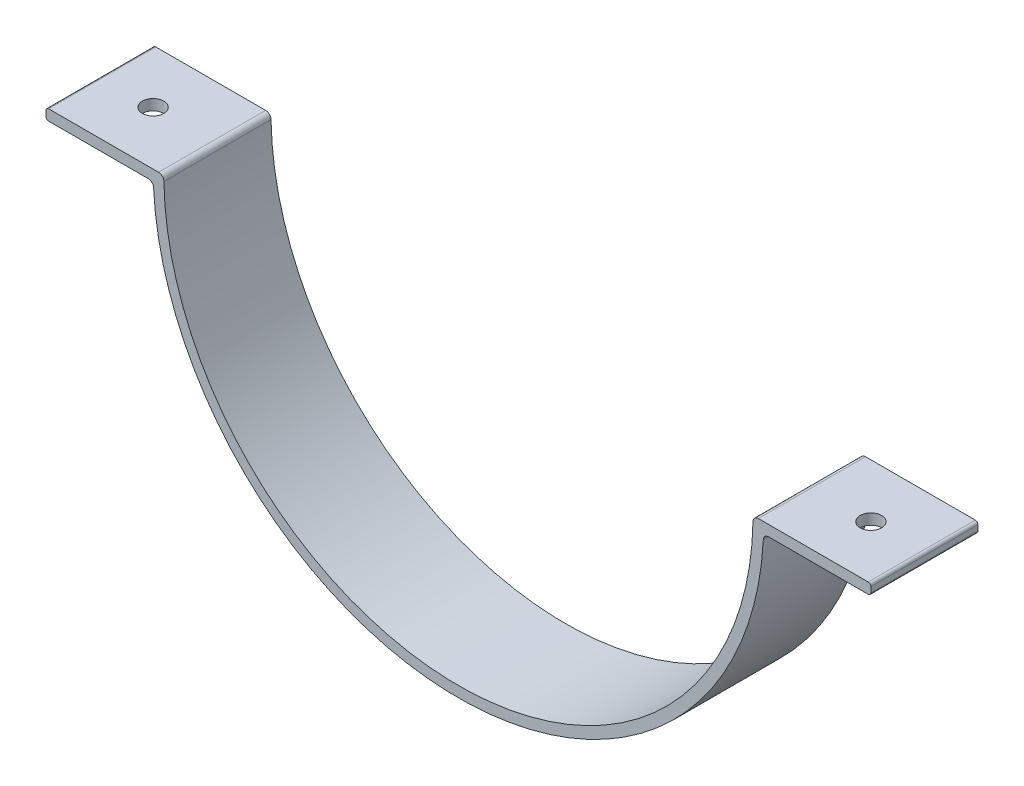
SolidWorks part; units mm, degrees
material "AISI 1020"
ref_plane "Alzado" through (0, 0, 0) normal (0, 0, 1) x (1, 0, 0)
ref_plane "Planta" through (0, 0, 0) normal (0, 1, 0) x (1, 0, 0)
ref_plane "Vista lateral" through (0, 0, 0) normal (1, 0, 0) x (0, 0, -1)
sketch "Croquis1" plane through (0, 0, 0) normal (0, 0, 1) x (1, 0, 0)
  line L2 (-57, 0) -> (-55.9911, 0)
  line L3 (-57, 0) -> (-76.5, 0)
  line L4 (-56.9649, 2) -> (56.9649, 2) construction
  line L5 (-77, -0.5) -> (-77, -1.5)
  line L6 (-76.5, -2) -> (-57.9224, -2)
  line L8 (-55, 0) -> (55, 0) construction
  line L9 (76.5, -2) -> (57.9224, -2)
  line L10 (77, -0.5) -> (77, -1.5)
  line L11 (57, 0) -> (76.5, 0)
  line L12 (57, 0) -> (55.9911, 0)
  arc A0 (-54.9912, -0.9821) -> (54.9912, -0.9821) centre (0, 0) ccw
  arc A1 (-56.9237, -2.9483) -> (56.9237, -2.9483) centre (0, 0) ccw
  arc A2 (-56.9649, 2) -> (56.9649, 2) centre (0, 0) ccw construction
  arc A3 (-56.9237, -2.9483) -> (-57.9224, -2) centre (-57.9224, -3) ccw
  arc A4 (-55, 0) -> (55, 0) centre (0, 0) ccw construction
  arc A5 (-54.9912, -0.9821) -> (-55.9911, 0) centre (-55.9911, -1) ccw
  arc A6 (-77, -0.5) -> (-76.5, 0) centre (-76.5, -0.5) cw
  arc A7 (-77, -1.5) -> (-76.5, -2) centre (-76.5, -1.5) ccw
  arc A8 (77, -1.5) -> (76.5, -2) centre (76.5, -1.5) cw
  arc A9 (77, -0.5) -> (76.5, 0) centre (76.5, -0.5) ccw
  arc A10 (54.9912, -0.9821) -> (55.9911, 0) centre (55.9911, -1) cw
  arc A11 (56.9237, -2.9483) -> (57.9224, -2) centre (57.9224, -3) cw
  point P19 (77, -2)
  point P21 (-77, 0)
  point P24 (-77, -2)
  point P37 (77, 0)
  dimension "D1" = 2
  dimension "D4" = 55
  dimension "D5" = 1
  dimension "D6" = 1
  dimension "D7" = 0.5
  dimension "D8" = 0.5
  dimension "D2" = 2
  dimension "D3" = 20
extrude "Saliente-Extruir2" add sketch "Croquis1" along normal blind 20
sketch "Croquis5" plane through (0, 0, 0) normal (0, 1, 0) x (1, 0, 0)
  line L0 (76.5, 0) -> (55.9911, 0) construction
  line L1 (77, -20) -> (77, 0) construction
  circle A0 centre (67, -10) radius 2
  dimension "D1" = 4
  dimension "D2" = 10
  dimension "D3" = 10
extrude "Cortar-Extruir2" cut sketch "Croquis5" against normal through all both and the other way through all
mirror "Simetría4" about plane through (0, 0, 0) normal (1, 0, 0) of "Cortar-Extruir2"
